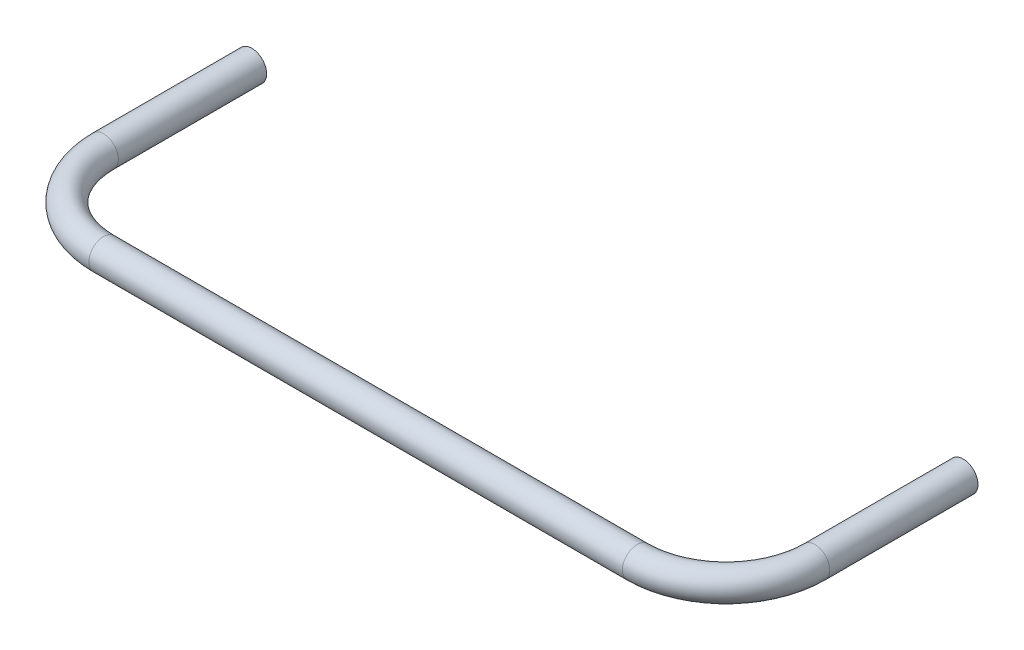
SolidWorks part; units mm, degrees
ref_plane "Front Plane" through (0, 0, 0) normal (0, 0, 1) x (1, 0, 0)
ref_plane "Top Plane" through (0, 0, 0) normal (0, 1, 0) x (1, 0, 0)
ref_plane "Right Plane" through (0, 0, 0) normal (1, 0, 0) x (0, 0, -1)
sketch "Sketch2" plane through (0, 0, 0) normal (0, 1, 0) x (1, 0, 0)
  line L0 (-114.3, 0) -> (114.3, 0)
  line L1 (152.4, 38.1) -> (152.4, 101.6)
  line L3 (0, -55) -> (0, 55) construction
  line L4 (-152.4, 38.1) -> (-152.4, 101.6)
  arc A0 (152.4, 38.1) -> (114.3, 0) centre (114.3, 38.1) cw
  arc A1 (-152.4, 38.1) -> (-114.3, 0) centre (-114.3, 38.1) ccw
  point P6 (152.4, 0)
  point P15 (0, 0)
  dimension "D3" = 38.1
  dimension "D1" = 152.4
  dimension "D2" = 101.6
sweep "Sweep1" add path "Sketch2" circular profile diameter 12.7 parameters "D3"=12.7
